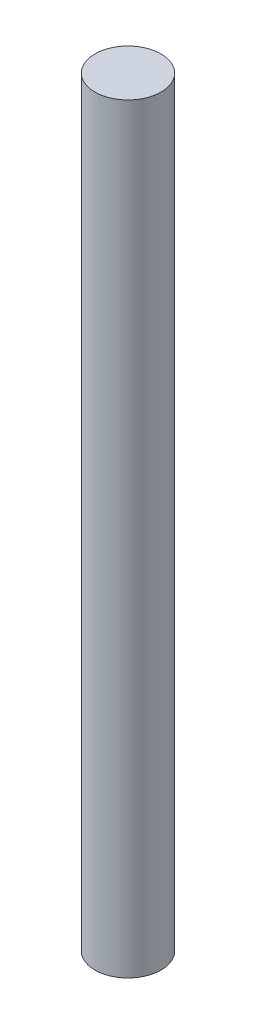
SolidWorks part; units mm, degrees
ref_plane "Front Plane" through (0, 0, 0) normal (0, 0, 1) x (1, 0, 0)
ref_plane "Top Plane" through (0, 0, 0) normal (0, 1, 0) x (1, 0, 0)
ref_plane "Right Plane" through (0, 0, 0) normal (1, 0, 0) x (0, 0, -1)
sketch "Sketch2" plane through (0, 0, 0) normal (0, 1, 0) x (1, 0, 0)
  circle A0 centre (0, 0) radius 4
  dimension "D1" = 8
extrude "Boss-Extrude1" add sketch "Sketch2" along normal blind 92
